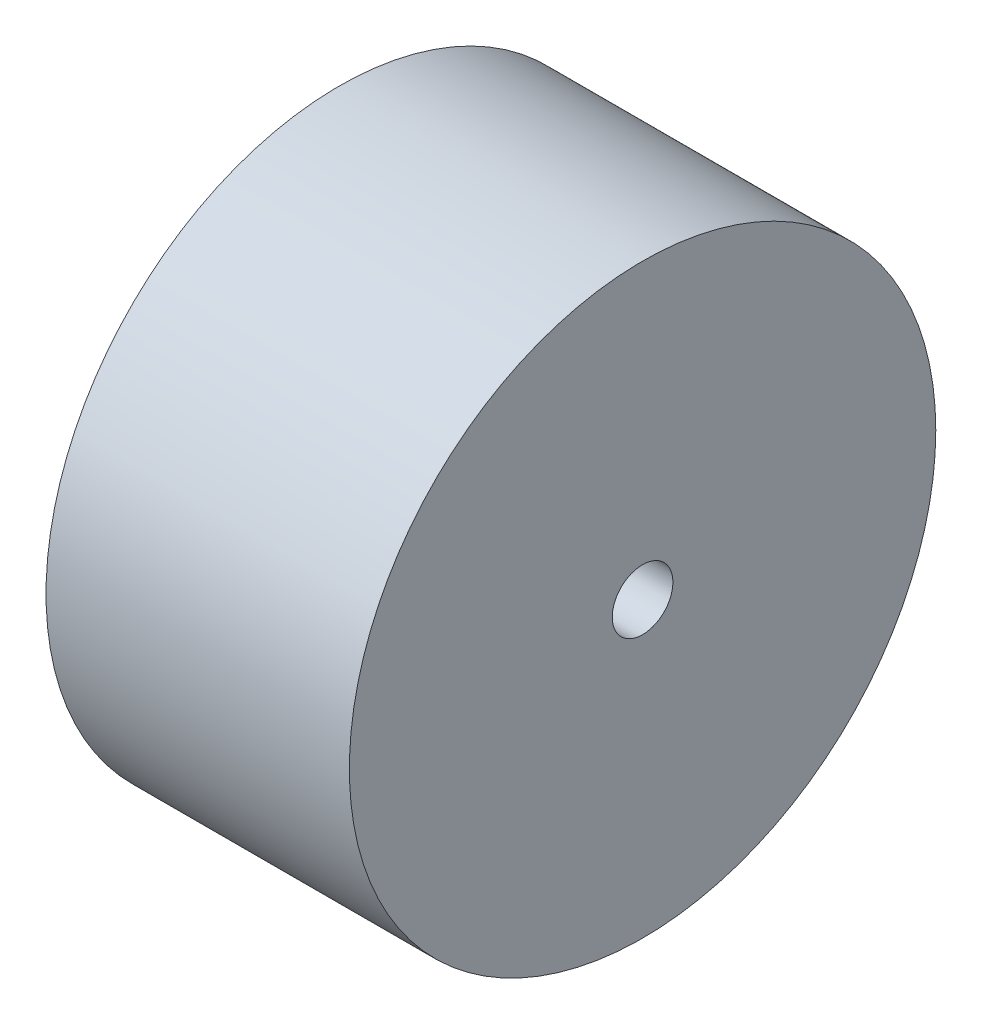
SolidWorks part; units mm, degrees
ref_plane "Front Plane" through (0, 0, 0) normal (0, 0, 1) x (1, 0, 0)
ref_plane "Top Plane" through (0, 0, 0) normal (0, 1, 0) x (1, 0, 0)
ref_plane "Right Plane" through (0, 0, 0) normal (1, 0, 0) x (0, 0, -1)
sketch "Sketch1" plane through (0, 0, 0) normal (1, 0, 0) x (0, 0, -1)
  circle A0 centre (0, 0) radius 29
  circle A1 centre (0, 0) radius 3
  dimension "D1" = 6
  dimension "D2" = 58
extrude "Boss-Extrude1" add sketch "Sketch1" along normal blind 30
